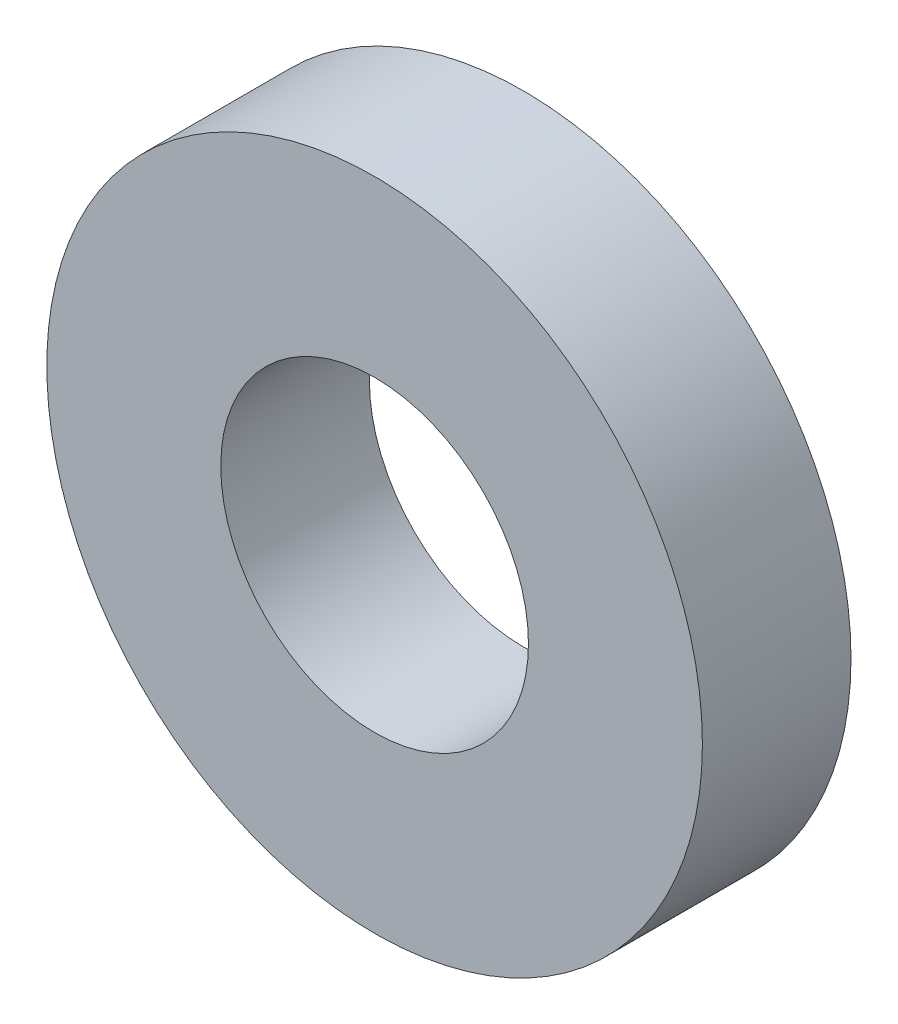
SolidWorks part; units mm, degrees
ref_plane "Ön Düzlem" through (0, 0, 0) normal (0, 0, 1) x (1, 0, 0)
ref_plane "Üst Düzlem" through (0, 0, 0) normal (0, 1, 0) x (1, 0, 0)
ref_plane "Sağ Düzlem" through (0, 0, 0) normal (1, 0, 0) x (0, 0, -1)
sketch "Sketch1" plane through (0, 0, 0) normal (0, 0, 1) x (1, 0, 0)
  circle A0 centre (0, 0) radius 17.6
  circle A1 centre (0, 0) radius 37.5
  dimension "D1" = 35.2
  dimension "D2" = 75
extrude "Boss-Extrude1" add sketch "Sketch1" along normal mid plane 17
